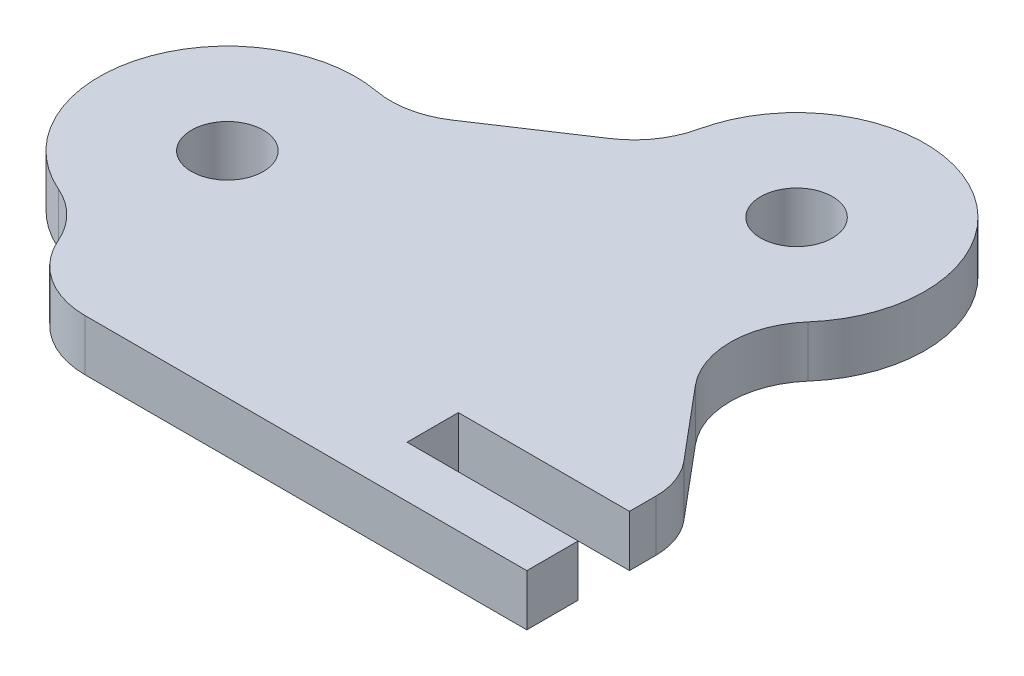
SolidWorks part; units mm, degrees
ref_plane "Front Plane" through (0, 0, 0) normal (0, 0, 1) x (1, 0, 0)
ref_plane "Top Plane" through (0, 0, 0) normal (0, 1, 0) x (1, 0, 0)
ref_plane "Right Plane" through (0, 0, 0) normal (1, 0, 0) x (0, 0, -1)
sketch "Sketch1" plane through (0, 0, 0) normal (0, 1, 0) x (1, 0, 0)
  line L0 (0, -11.4564) -> (0, -12.5)
  line L1 (0, -12.5) -> (30, -12.5)
  line L2 (30, -12.5) -> (30, -4.9559)
  line L3 (29.0642, -2.3847) -> (25.5555, 1.7968)
  line L4 (0, 0) -> (20, 13.2665) construction
  line L5 (5.0178, 8.1284) -> (10.56, 11.8047)
  line L7 (-2.2111, 3.3333) -> (17.7889, 16.5998) construction
  circle A0 centre (0, 0) radius 2.1
  arc A1 (1.3524, 7.3771) -> (-3, -6.8739) centre (0, 0) ccw
  circle A2 centre (20, 13.2665) radius 2.1
  arc A3 (25.6314, 8.313) -> (12.6777, 14.8894) centre (20, 13.2665) ccw
  arc A4 (5.0178, 8.1284) -> (1.3524, 7.3771) centre (2.254, 12.2951) cw
  arc A5 (10.56, 11.8047) -> (12.6777, 14.8894) centre (7.7962, 15.9714) ccw
  arc A6 (25.5555, 1.7968) -> (25.6314, 8.313) centre (29.3857, 5.0107) cw
  arc A7 (0, -11.4564) -> (-3, -6.8739) centre (-5, -11.4564) ccw
  arc A8 (30, -4.9559) -> (29.0642, -2.3847) centre (26, -4.9559) ccw
  point P26 (0, -7.5)
  point P29 (30, -3.5)
  dimension "D1" = 4.2
  dimension "D2" = 15
  dimension "D3" = 4.2
  dimension "D4" = 15
  dimension "D12" = 5
  dimension "D13" = 5
  dimension "D14" = 5
  dimension "D15" = 5
  dimension "D16" = 4
  dimension "D5" = 24
  dimension "D6" = 20
  dimension "D7" = 5
  dimension "D8" = 30
  dimension "D9" = 9
  dimension "D10" = 50
  dimension "D11" = 4
extrude "Boss-Extrude1" add sketch "Sketch1" along normal blind 3
fillet "Fillet1" radius 5 1 edges at (0, 1.5, 12.5)
sketch "Sketch2" plane through (0, 3, 0) normal (0, 1, 0) x (1, 0, 0)
  line L0 (30, -12.5) -> (30, -4.9559) construction
  line L1 (30, -6.5) -> (20, -6.5)
  line L2 (30, -6.5) -> (30, -9.5)
  line L3 (30, -9.5) -> (20, -9.5)
  line L4 (20, -6.5) -> (20, -9.5)
  line L5 (4.184, -12.5) -> (30, -12.5) construction
  dimension "D1" = 3
  dimension "D2" = 10
  dimension "D3" = 3
extrude "Cut-Extrude1" cut sketch "Sketch2" against normal blind 3
